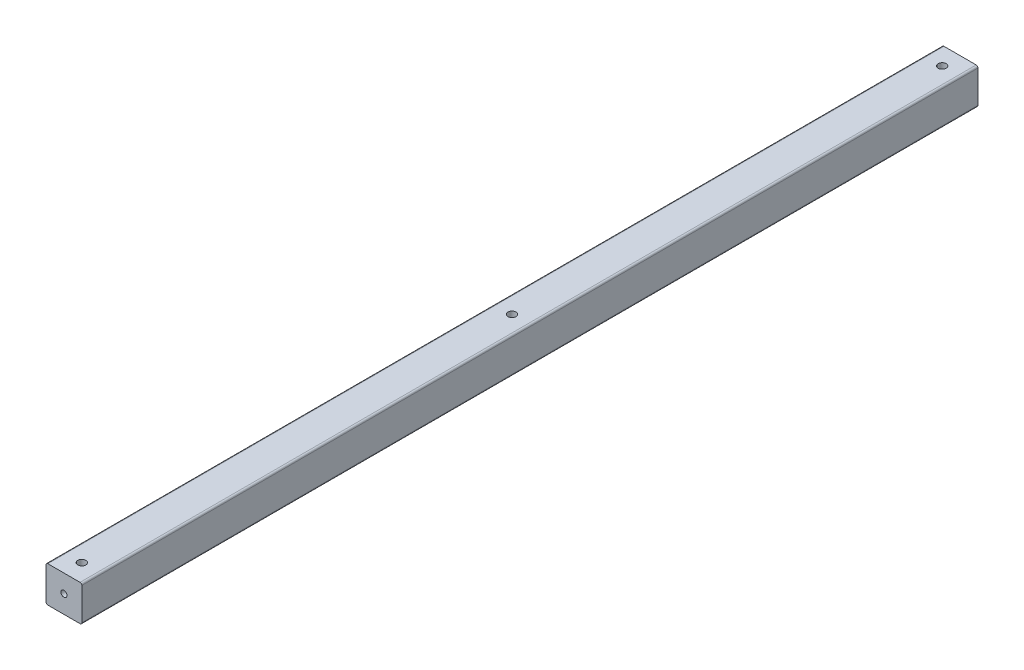
SolidWorks part; units mm, degrees
ref_plane "Front Plane" through (0, 0, 0) normal (0, 0, 1) x (1, 0, 0)
ref_plane "Top Plane" through (0, 0, 0) normal (0, 1, 0) x (1, 0, 0)
ref_plane "Right Plane" through (0, 0, 0) normal (1, 0, 0) x (0, 0, -1)
sketch "Sketch1" plane through (0, 0, 0) normal (0, 0, 1) x (1, 0, 0)
  line L1 (-20, -20) -> (20, -20)
  line L2 (-20, -20) -> (-20, 20)
  line L3 (-20, 20) -> (20, 20)
  line L4 (20, -20) -> (20, 20)
  line L5 (-20, -20) -> (20, 20) construction
  line L6 (-20, 20) -> (20, -20) construction
  circle A0 centre (0, 0) radius 2.5
  point P0 (0, 0)
  dimension "D3" = 5
  dimension "D1" = 40
  dimension "D2" = 40
extrude "Boss-Extrude1" add sketch "Sketch1" along normal mid plane 1000
fillet "Fillet1" radius 2 4 edges at (20, -20, 0) (-20, -20, 0) (-20, 20, 0) (20, 20, 0)
sketch "Sketch2" plane through (0, 20, 0) normal (0, 1, 0) x (1, 0, 0)
  line L0 (0, 958.3172) -> (0, -945.7078) construction
  line L2 (18, 500) -> (-18, 500) construction
  line L3 (18, -500) -> (-18, -500) construction
  point P3 (0, -100)
  point P4 (0, 100)
  dimension "D1" = 600
  dimension "D2" = 600
hole_wizard "Ø4.5 (4.5) Diameter Hole1" positions "Sketch3" profile "Sketch4" hole size "Ø4.5" standard "ISO"
sketch "Sketch3" plane through (0, 20, 0) normal (0, 1, 0) x (1, 0, 0)
  point P0 (0, -300)
  point P3 (0, 300)
sketch "Sketch4" plane through (0, 20, 300) normal (1, 0, 0) x (0, 0, 1)
  line L0 (0, 0) -> (0, 40)
  line L1 (0, 40) -> (2.25, 40)
  line L2 (2.25, 40) -> (2.25, 0)
  line L5 (2.25, 0) -> (0, 0)
  line L11 (0, -6.35) -> (0, 107.95) construction
  dimension "Thru Hole Dia." = 4.5
  dimension "Thru Hole Depth" = 40
sketch "Sketch5" plane through (0, -20, 0) normal (0, -1, 0) x (1, 0, 0)
  line L0 (0, 500) -> (0, -1000.0028) construction
  line L1 (-18, 500) -> (18, 500) construction
  line L2 (-18, -500) -> (18, -500) construction
  point P4 (0, 480)
  point P5 (0, 500)
  point P6 (0, 0)
  point P7 (0, -500)
  point P8 (0, -480)
  dimension "D1" = 500
  dimension "D2" = 500
  dimension "D3" = 20
  dimension "D4" = 20
hole_wizard "CBORE for M8 Hex Socket Head Cap Screw1" positions "Sketch6" profile "Sketch7" counterbore size "M8" standard "ISO"
sketch "Sketch6" plane through (0, -20, 0) normal (0, -1, 0) x (-1, 0, 0)
  point P0 (0, 500)
  point P3 (0, 0)
  point P6 (0, -500)
  point P9 (0, 480)
  point P12 (0, -480)
sketch "Sketch7" plane through (0, -20, 480) normal (1, 0, 0) x (0, 0, -1)
  line L0 (0, 0) -> (0, 40)
  line L1 (0, 40) -> (4.5, 40)
  line L3 (4.5, 40) -> (4.5, 8.6)
  line L4 (4.5, 8.6) -> (7.5, 8.6)
  line L5 (7.5, 8.6) -> (7.5, 0)
  line L7 (7.5, 0) -> (0, 0)
  line L11 (0, -6.35) -> (0, 107.95) construction
  dimension "Thru Hole Dia." = 9
  dimension "Thru Hole Depth" = 40
  dimension "C'Bore Dia." = 15
  dimension "C'Bore Depth" = 8.6
hole_wizard "M8x1.25 Tapped Hole1" positions "Sketch8" profile "Sketch9" tap size "M8x1.25" standard "ANSI Metric"
sketch "Sketch8" plane through (0, 0, 500) normal (0, 0, 1) x (1, 0, 0)
  point P0 (0, 0)
sketch "Sketch9" plane through (0, 0, 500) normal (1, 0, 0) x (0, -1, 0)
  line L0 (0, 0) -> (0, 29.7929)
  line L1 (0, 29.7929) -> (3.4, 27.75)
  line L2 (3.4, 27.75) -> (3.4, 0)
  line L5 (3.4, 0) -> (0, 0)
  line L10 (0, 29.7929) -> (-3.4, 27.75) construction
  line L11 (0, -6.35) -> (0, 107.95) construction
  dimension "Tap Drill Dia." = 6.8
  dimension "Tap Drill Depth" = 27.75
  dimension "Drill Angle" = 118
cosmetic thread "Hole Thread1"
mirror "Mirror1" about plane through (0, 0, 0) normal (0, 0, 1) of "M8x1.25 Tapped Hole1"
cosmetic thread "Hole Thread2"
